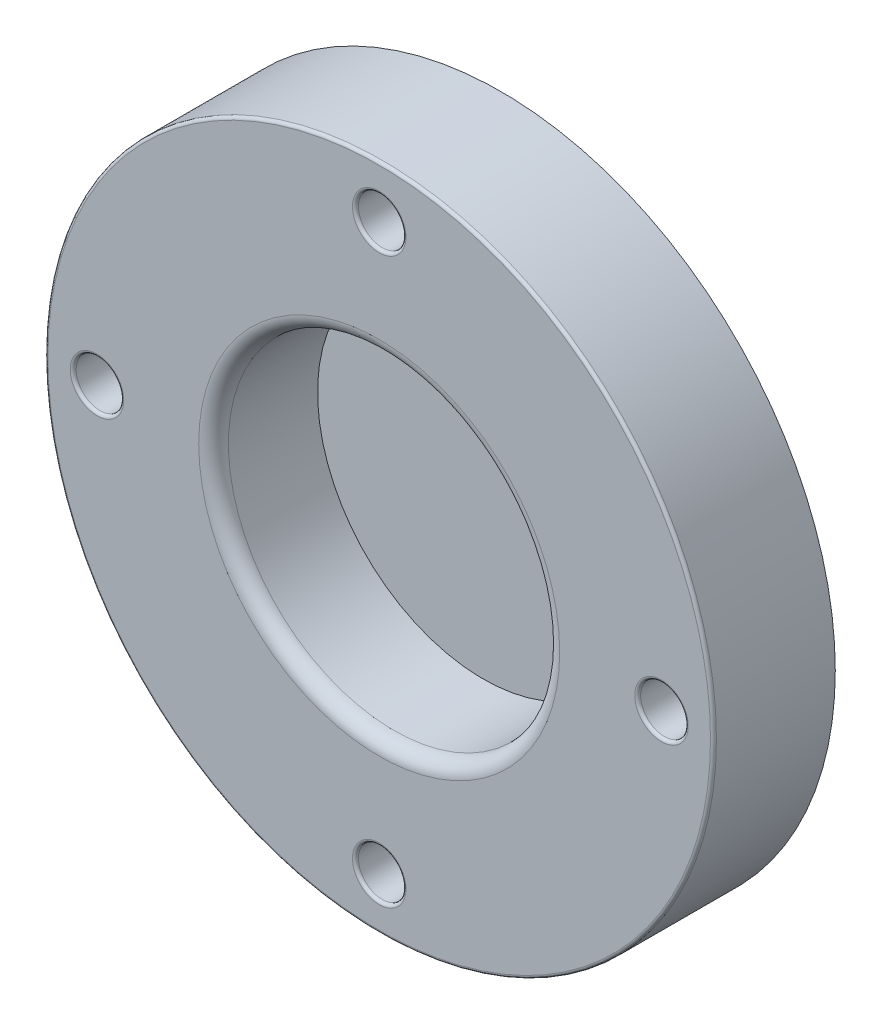
SolidWorks part; units mm, degrees
ref_plane "Front" through (0, 0, 0) normal (0, 0, 1) x (1, 0, 0)
ref_plane "Top" through (0, 0, 0) normal (0, 1, 0) x (1, 0, 0)
ref_plane "Right" through (0, 0, 0) normal (1, 0, 0) x (0, 0, -1)
sketch "Sketch1" plane through (0, 0, 0) normal (0, 0, 1) x (1, 0, 0)
  circle A0 centre (0, 0) radius 22.5
  dimension "D1" = 45
extrude "Boss-Extrude1" add sketch "Sketch1" along normal blind 8.2
sketch "Sketch2" plane through (0, 0, 8.2) normal (0, 0, 1) x (1, 0, 0)
  circle A0 centre (0, 0) radius 11.15
  dimension "D1" = 22.3
extrude "Cut-Extrude1" cut sketch "Sketch2" against normal blind 7
sketch "Sketch3" plane through (0, 0, 8.2) normal (0, 0, 1) x (1, 0, 0)
  circle A0 centre (-19, 0) radius 1.6
  circle A1 centre (0, 19) radius 1.6
  circle A2 centre (19, 0) radius 1.6
  circle A3 centre (0, -19) radius 1.6
  point P12 (0, 0)
  dimension "D1" = 3.2
  dimension "D2" = 19
  dimension "D3" = 4
extrude "Cut-Extrude2" cut sketch "Sketch3" against normal through all
fillet "Fillet1" radius 1 1 edges at (11.15, 0, 8.2)
fillet "Fillet2" radius 0.2 5 edges at (-17.4, 0, 8.2) (1.6, 19, 8.2) (20.6, 0, 8.2) (1.6, -19, 8.2) (22.5, 0, 8.2)
